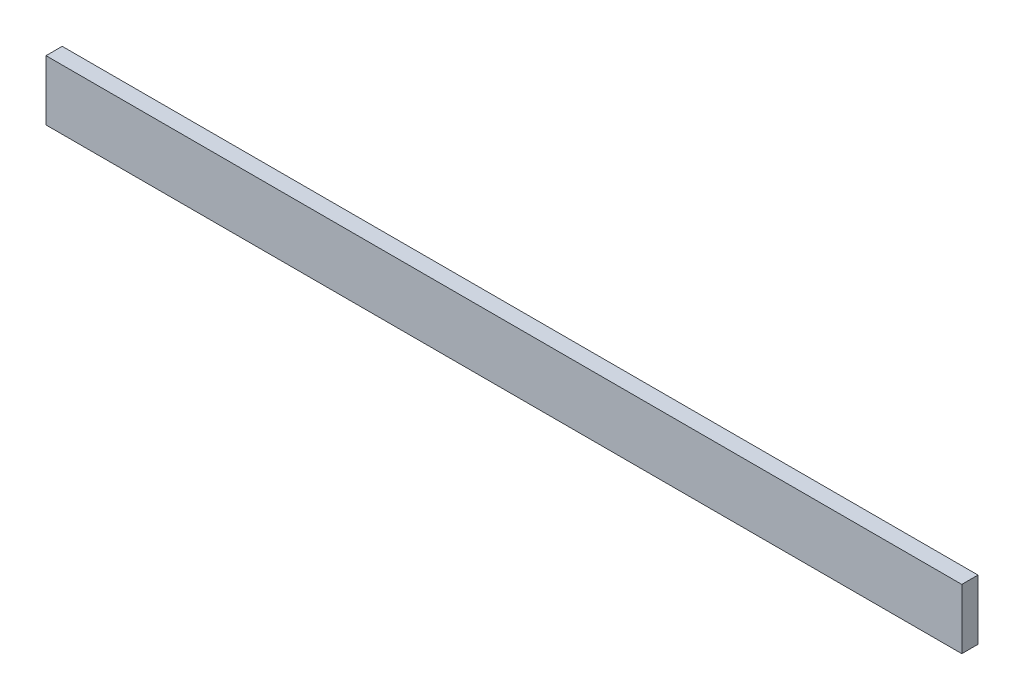
SolidWorks part; units mm, degrees
ref_plane "Front" through (0, 0, 0) normal (0, 0, 1) x (1, 0, 0)
ref_plane "Top" through (0, 0, 0) normal (0, 1, 0) x (1, 0, 0)
ref_plane "Right" through (0, 0, 0) normal (1, 0, 0) x (0, 0, -1)
sketch "Esquisse1" plane through (0, 0, 0) normal (0, 0, 1) x (1, 0, 0)
  line L1 (0, 0) -> (1526, 0)
  line L2 (0, 0) -> (0, 100)
  line L3 (0, 100) -> (1526, 100)
  line L4 (1526, 0) -> (1526, 100)
  dimension "D1" = 1526
  dimension "D2" = 100
extrude "Boss.-Extru.1" add sketch "Esquisse1" along normal blind 27
